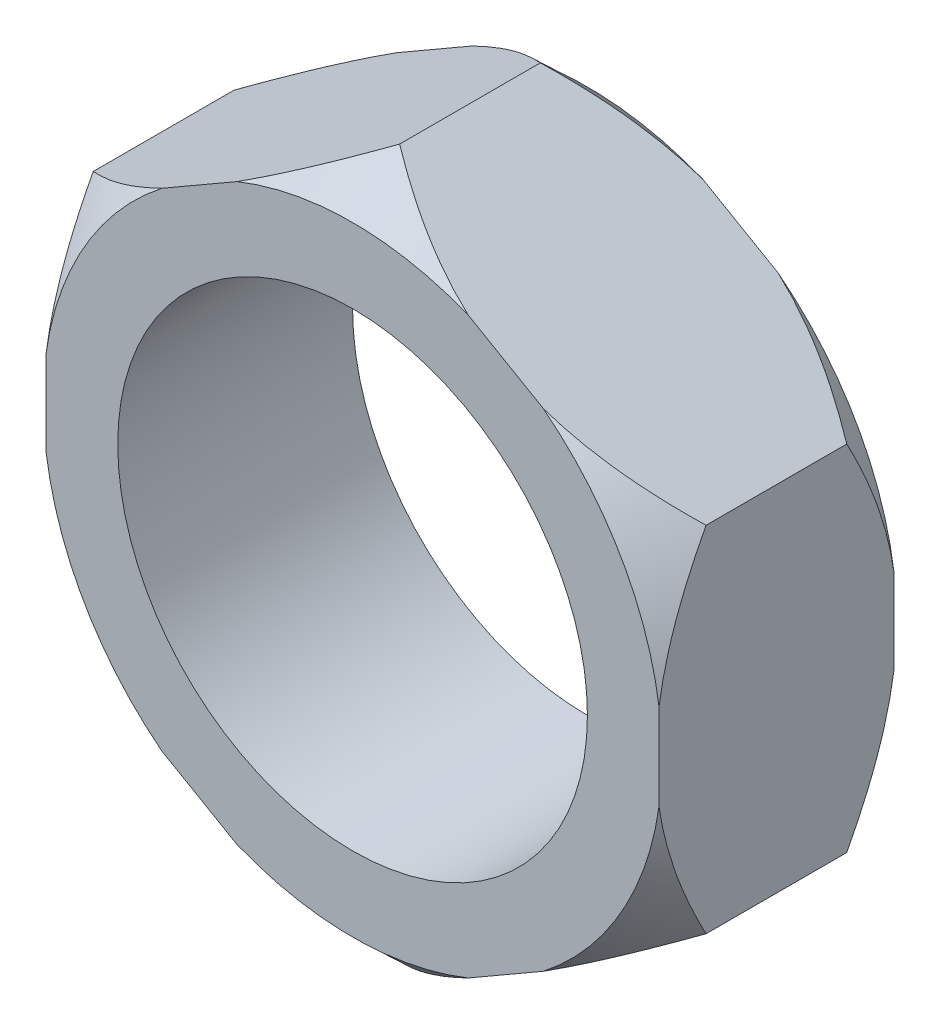
SolidWorks part; units mm, degrees
ref_plane "前视基准面" through (0, 0, 0) normal (0, 0, 1) x (1, 0, 0)
ref_plane "上视基准面" through (0, 0, 0) normal (0, 1, 0) x (1, 0, 0)
ref_plane "右视基准面" through (0, 0, 0) normal (1, 0, 0) x (0, 0, -1)
sketch "草图1" plane through (0, 0, 0) normal (0, 0, 1) x (1, 0, 0)
  line L1 (0, 2.26) -> (-1.9572, 1.13)
  line L2 (-1.9572, 1.13) -> (-1.9572, -1.13)
  line L3 (-1.9572, -1.13) -> (0, -2.26)
  line L4 (0, -2.26) -> (1.9572, -1.13)
  line L5 (1.9572, -1.13) -> (1.9572, 1.13)
  line L6 (1.9572, 1.13) -> (0, 2.26)
  circle A0 centre (0, 0) radius 1.5
  circle A1 centre (0, 0) radius 1.9572 construction
extrude "凸台-拉伸1" add sketch "草图1" along normal blind 1.5
ref_axis "基准轴1" through (0, 0, 1.5) along (0, 0, -1)
sketch "草图2" plane through (0, 0, 0) normal (1, 0, 0) x (0, 0, -1)
  line L0 (-1.1994, 2.26) -> (-1.5694, 1.9112)
  line L1 (-1.5, 2.26) -> (0, 2.26) construction
  line L2 (-1.5694, 1.9112) -> (-1.5694, 2.3849)
  line L3 (-1.5694, 2.3849) -> (-1.1897, 2.3849)
  line L4 (-1.1897, 2.3849) -> (-1.1994, 2.26)
  point P5 (-1.5694, 1.9112)
  point P7 (0, 0)
revolve "切除-旋转1" cut sketch "草图2" angle 360 about axis through (0, 0, 1.5) along (0, 0, -1)
ref_plane "基准面1" through (0, 0, 0.75) normal (0, 0, -1) x (-1, 0, 0)
mirror "镜向1" about plane through (0, 0, 0.75) normal (0, 0, -1) of "切除-旋转1"
